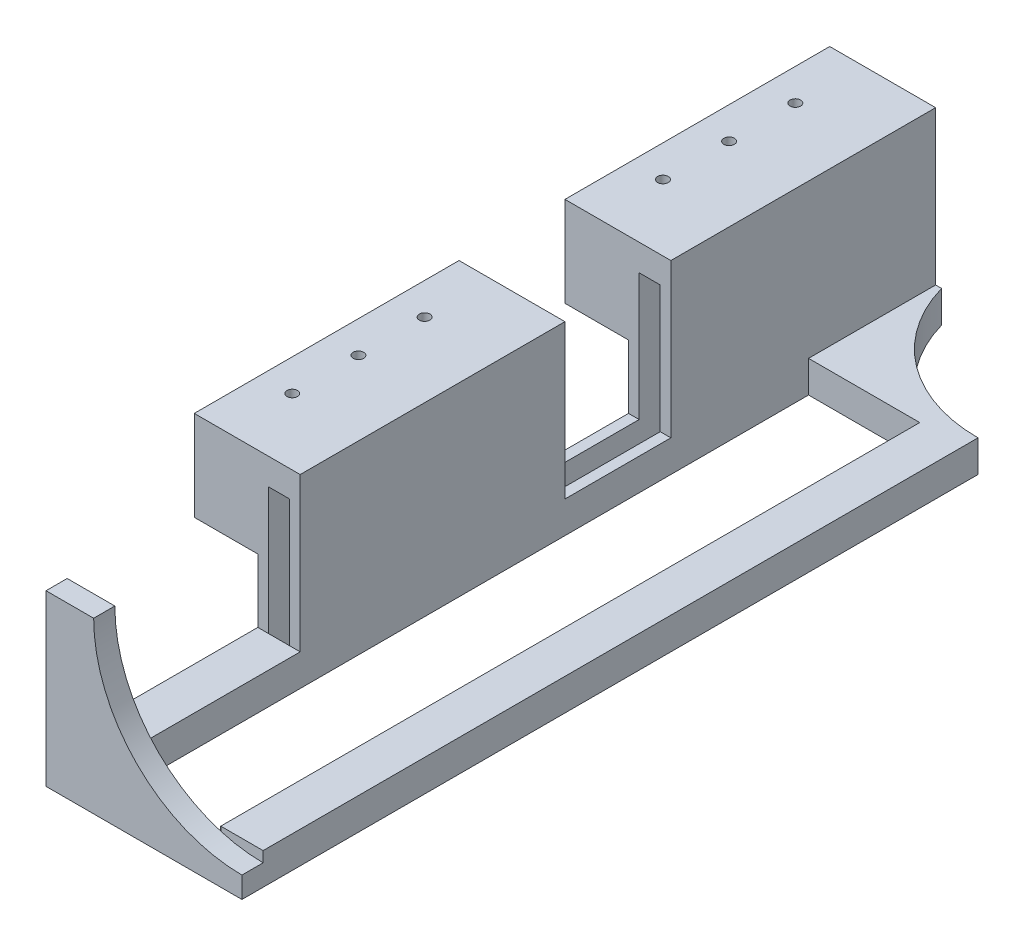
SolidWorks part; units mm, degrees
ref_plane "Alzado" through (0, 0, 0) normal (0, 0, 1) x (1, 0, 0)
ref_plane "Planta" through (0, 0, 0) normal (0, 1, 0) x (1, 0, 0)
ref_plane "Vista lateral" through (0, 0, 0) normal (1, 0, 0) x (0, 0, -1)
sketch "Croquis2" plane through (0, 0, 0) normal (0, 0, 1) x (1, 0, 0)
  line L0 (-4.5963, 11.5024) -> (-4.5963, -1.4976)
  line L1 (-8.5963, 11.5024) -> (-4.5963, 11.5024)
  line L2 (-8.5963, 11.5024) -> (-8.5963, -4.4976)
  line L3 (-8.5963, -4.4976) -> (-4.5963, -4.4976)
  line L9 (-4.5963, -4.4976) -> (9.9037, -4.4976)
  line L11 (-4.5963, -1.4976) -> (9.9037, -1.4976)
  line L12 (9.9037, -4.4976) -> (9.9037, -1.4976)
  dimension "D1" = 13
  dimension "D5" = 3
extrude "Saliente-Extruir1" add sketch "Croquis2" along normal blind 82
sketch "Croquis3" plane through (0, 11.5024, 0) normal (0, 1, 0) x (1, 0, 0)
  line L0 (-4.5963, -82) -> (-4.5963, 0) construction
  line L1 (-4.5963, -29) -> (-14.5963, -29)
  line L2 (-4.5963, -29) -> (-4.5963, -4)
  line L3 (-4.5963, -4) -> (-14.5963, -4)
  line L4 (-14.5963, -29) -> (-14.5963, -4)
  line L5 (-4.5963, -82) -> (-4.5963, 0) construction
  line L6 (-4.5963, -64) -> (-14.5963, -64)
  line L7 (-4.5963, -64) -> (-4.5963, -39)
  line L8 (-4.5963, -39) -> (-14.5963, -39)
  line L9 (-14.5963, -64) -> (-14.5963, -39)
  line L10 (9.9037, 0) -> (-4.5963, 0) construction
  line L11 (-4.5963, -82) -> (-8.5963, -82) construction
  dimension "D1" = 4
  dimension "D2" = 18
  dimension "D3" = 25
  dimension "D4" = 25
  dimension "D5" = 10
  dimension "D6" = 10
extrude "Saliente-Extruir2" add sketch "Croquis3" along normal blind 1.5
sketch "Croquis4" plane through (0, 0, 82) normal (0, 0, 1) x (1, 0, 0)
  line L0 (9.9037, -4.4976) -> (9.9037, -1.4976) construction
  line L1 (-8.5963, -4.4976) -> (9.9037, -4.4976)
  line L2 (-8.5963, -4.4976) -> (-8.5963, 11.5024)
  line L3 (-8.5963, 11.5024) -> (9.9037, 11.5024)
  line L4 (9.9037, -4.4976) -> (9.9037, 11.5024)
  line L6 (-4.5963, 11.5024) -> (-8.5963, 11.5024) construction
extrude "Saliente-Extruir3" add sketch "Croquis4" along normal blind 2
sketch "Croquis5" plane through (0, -1.4976, 0) normal (0, 1, 0) x (1, 0, 0)
  circle A0 centre (9.9037, 0) radius 14.5
extrude "Cortar-Extruir1" cut sketch "Croquis5" against normal through all
sketch "Croquis13" plane through (-8.5963, 0, 0) normal (-1, 0, 0) x (0, 0, 1)
  line L0 (84, 11.5024) -> (84, -4.4976) construction
  line L1 (4, 11.5024) -> (-3.6728, 11.5024)
  line L2 (4, 11.5024) -> (4, -6.968)
  line L3 (4, -6.968) -> (-3.6728, -6.968)
  line L4 (-3.6728, 11.5024) -> (-3.6728, -6.968)
  line L5 (29, 11.5024) -> (39, 11.5024)
  line L6 (29, 11.5024) -> (29, -1.4976)
  line L7 (29, -1.4976) -> (39, -1.4976)
  line L8 (39, 11.5024) -> (39, -1.4976)
  line L9 (64, 11.5024) -> (82, 11.5024)
  line L10 (64, 11.5024) -> (64, -1.4976)
  line L11 (64, -1.4976) -> (82, -1.4976)
  line L12 (82, 11.5024) -> (82, -1.4976)
  line L13 (84, -4.4976) -> (0, -4.4976) construction
  line L14 (39, 13.0024) -> (39, 11.5024) construction
  dimension "D1" = 2
  dimension "D2" = 3
  dimension "D3" = 3
extrude "Cortar-Extruir9" cut sketch "Croquis13" against normal blind 13
sketch "Croquis14" plane through (0, 0, 84) normal (0, 0, 1) x (1, 0, 0)
  line L0 (9.9037, 11.5024) -> (-8.5963, 11.5024) construction
  line L1 (9.9037, -4.4976) -> (9.9037, 11.5024) construction
  line L2 (-4.0963, 11.5024) -> (9.9037, 11.5024)
  line L3 (9.9037, 11.5024) -> (9.9037, -2.4976)
  arc A0 (-4.0963, 11.5024) -> (9.9037, -2.4976) centre (9.9037, 11.5024) ccw
  dimension "D1" = 14
extrude "Cortar-Extruir10" cut sketch "Croquis14" against normal blind 2
sketch "Croquis15" plane through (0, 0, 4) normal (0, 0, -1) x (-1, 0, 0)
  line L0 (6.5963, -4.4976) -> (6.5963, 11.5024) construction
  line L1 (8.5963, -4.4976) -> (4.0336, -4.4976) construction
  line L2 (11.4673, 11.5024) -> (-32.2747, 11.5024) construction
  line L3 (8.5963, -4.4976) -> (8.5963, 11.5024) construction
  line L5 (5.6009, -3.4976) -> (7.5916, -3.4976)
  line L6 (5.6009, -3.4976) -> (5.6009, 10.5024)
  line L7 (5.6009, 10.5024) -> (7.5916, 10.5024)
  line L8 (7.5916, -3.4976) -> (7.5916, 10.5024)
  line L9 (5.6009, -3.4976) -> (7.5916, 10.5024) construction
  line L10 (5.6009, 10.5024) -> (7.5916, -3.4976) construction
  point P8 (6.5963, 3.5024)
  dimension "D1" = 2
  dimension "D2" = 1
  dimension "D3" = 1.0047
extrude "Cortar-Extruir11" cut sketch "Croquis15" against normal blind 60
sketch "Croquis16" plane through (0, -4.4976, 0) normal (0, -1, 0) x (1, 0, 0)
  line L0 (0.6537, 84) -> (0.6537, 14) construction
  line L1 (-8.5963, 84) -> (9.9037, 84) construction
  line L2 (9.9037, 84) -> (9.9037, 14.5) construction
  line L3 (-4.5963, 16) -> (5.9037, 16)
  line L4 (-4.5963, 16) -> (-4.5963, 82)
  line L5 (-4.5963, 82) -> (5.9037, 82)
  line L6 (5.9037, 16) -> (5.9037, 82)
  line L7 (-4.5963, 16) -> (5.9037, 82) construction
  line L8 (-4.5963, 82) -> (5.9037, 16) construction
  point P4 (0.6537, 49)
  dimension "D1" = 70
  dimension "D2" = 2
  dimension "D3" = 4
extrude "Cortar-Extruir12" cut sketch "Croquis16" against normal blind 10
sketch "Croquis19" plane through (0, 11.5024, 0) normal (0, -1, 0) x (1, 0, 0)
  line L1 (-14.5963, 29) -> (-8.5963, 29)
  line L2 (-14.5963, 29) -> (-14.5963, 4)
  line L3 (-14.5963, 4) -> (-8.5963, 4)
  line L4 (-8.5963, 29) -> (-8.5963, 4)
  line L5 (-14.5963, 39) -> (-8.5963, 39)
  line L6 (-14.5963, 39) -> (-14.5963, 64)
  line L7 (-14.5963, 64) -> (-8.5963, 64)
  line L8 (-8.5963, 39) -> (-8.5963, 64)
extrude "Saliente-Extruir7" add sketch "Croquis19" along normal blind 7
sketch "Croquis23" plane through (0, 4.5024, 0) normal (0, -1, 0) x (1, 0, 0)
  line L0 (-11.5963, 45.25) -> (-11.5963, 57.75) construction
  line L2 (-8.5963, 84) -> (-8.5963, 4) construction
  line L4 (-8.5963, 64) -> (-14.5963, 64) construction
  line L5 (-14.5963, 39) -> (-8.5963, 39) construction
  circle A0 centre (-11.5963, 45.25) radius 0.5
  circle A1 centre (-11.5963, 57.75) radius 0.5
  circle A2 centre (-11.5963, 51.5) radius 0.5
  dimension "D4" = 1
  dimension "D5" = 1
  dimension "D6" = 1
  dimension "D1" = 3
  dimension "D2" = 6.25
  dimension "D3" = 6.25
extrude "Cortar-Extruir13" cut sketch "Croquis23" against normal through all both and the other way through all
ref_plane "Plano1" through (0, 0, 34) normal (0, 0, -1) x (-1, 0, 0)
mirror "Simetría1" about plane through (0, 0, 34) normal (0, 0, -1) of "Cortar-Extruir13"
